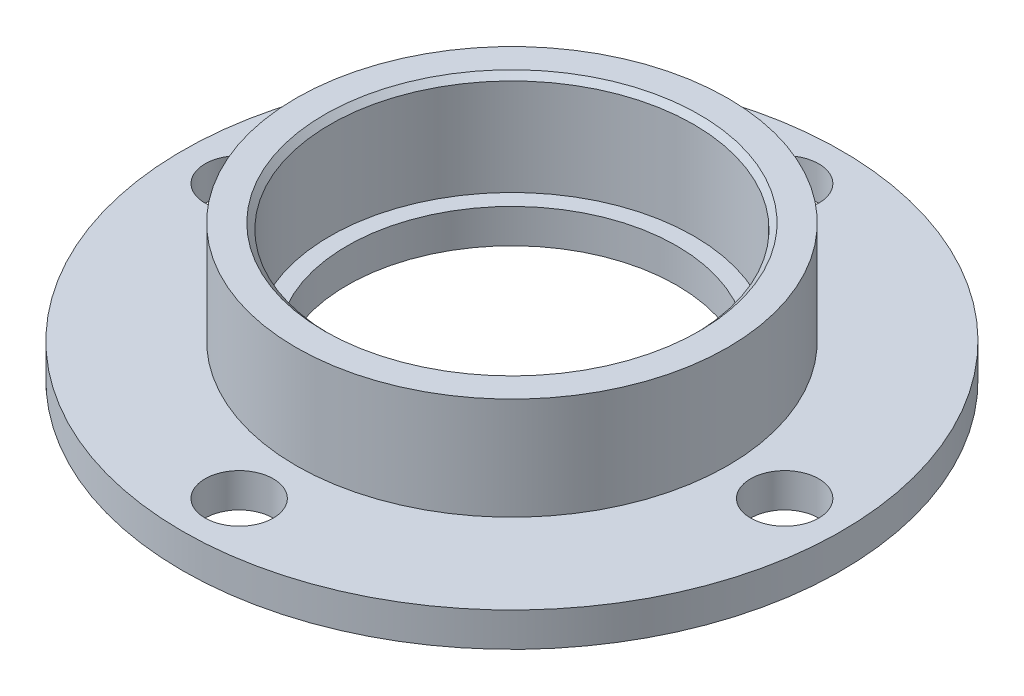
SolidWorks part; units mm, degrees
material "AISI 316 Stainless Steel Sheet (SS)"
ref_plane "Front Plane" through (0, 0, 0) normal (0, 0, 1) x (1, 0, 0)
ref_plane "Top Plane" through (0, 0, 0) normal (0, 1, 0) x (1, 0, 0)
ref_plane "Right Plane" through (0, 0, 0) normal (1, 0, 0) x (0, 0, -1)
sketch "Sketch1" plane through (0, 0, 0) normal (0, 1, 0) x (1, 0, 0)
  line L0 (0, -44.7868) -> (0, 44.7868) construction
  circle A0 centre (0, 0) radius 29
  circle A1 centre (0, 0) radius 14.5
  circle A2 centre (0, 24) radius 1
  circle A3 centre (24, 0) radius 1
  circle A4 centre (0, -24) radius 1
  circle A5 centre (-24, 0) radius 1
  point P17 (0, 0)
  dimension "D1" = 58
  dimension "D2" = 2
  dimension "D4" = 29
  dimension "D5" = 24
  dimension "D3" = 4
extrude "Boss-Extrude1" add sketch "Sketch1" along normal blind 3
sketch "Sketch2" plane through (0, 3, 0) normal (0, 1, 0) x (1, 0, 0)
  circle A0 centre (0, 0) radius 19
  circle A2 centre (0, 0) radius 16
  dimension "D1" = 38
  dimension "D2" = 32
extrude "Boss-Extrude2" add sketch "Sketch2" along normal blind 9
sketch "Sketch7" plane through (0, 3, 0) normal (0, 1, 0) x (1, 0, 0)
  point P0 (0, 24)
  point P3 (24, 0)
  point P6 (0, -24)
  point P9 (-24, 0)
hole_wizard "Ø6.0mm Dowel Hole1" positions "Sketch7" profile "Sketch6" hole size "Ø6.0" standard "ANSI Metric" end condition through all
sketch "Sketch6" plane through (0, 3, -24) normal (1, 0, 0) x (0, 0, 1)
  line L0 (0, 0) -> (0, 3)
  line L1 (0, 3) -> (3, 3)
  line L2 (3, 3) -> (3, 0)
  line L5 (3, 0) -> (0, 0)
  line L11 (0, -6.35) -> (0, 107.95) construction
  dimension "Thru Hole Dia." = 6
  dimension "Thru Hole Depth" = 3
chamfer "Chamfer1" distance 0.5 angle 45 1 edges at (0, 12, 16)
sketch "Sketch8" plane through (0, 0, 0) normal (1, 0, 0) x (0, 0, -1)
  line L0 (-32.6186, 7) -> (25.473, 7)
  line L1 (29, 3) -> (-29, 3) construction
  dimension "D1" = 4
split line "Split Line1"
